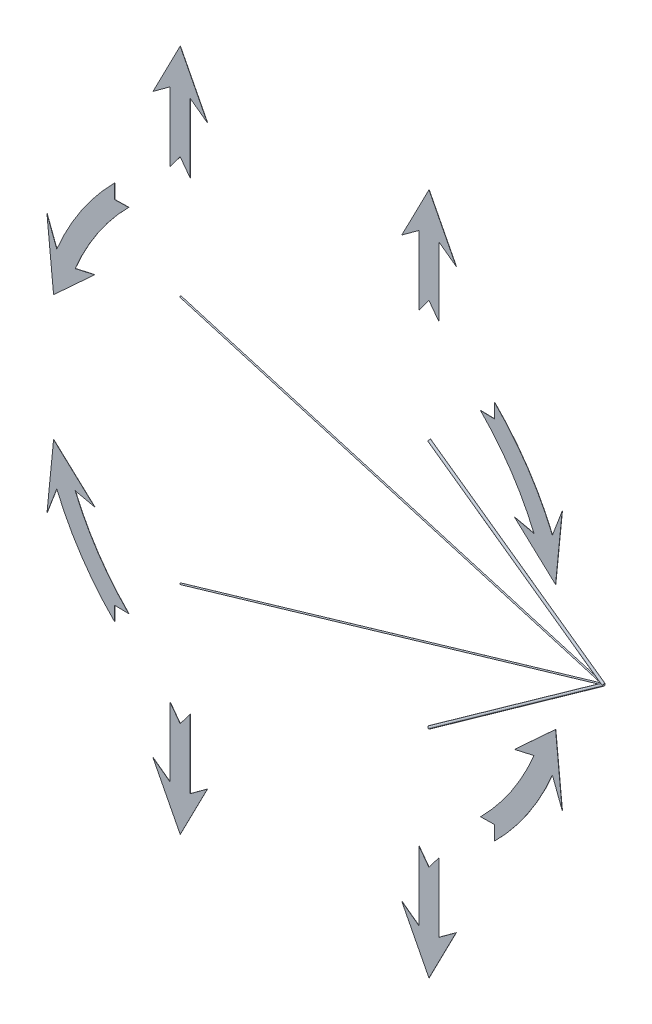
SolidWorks part; units mm, degrees
ref_plane "前视基准面" through (0, 0, 0) normal (0, 0, 1) x (1, 0, 0)
ref_plane "上视基准面" through (0, 0, 0) normal (0, 1, 0) x (1, 0, 0)
ref_plane "右视基准面" through (0, 0, 0) normal (1, 0, 0) x (0, 0, -1)
other "Configuration Table"
sketch "草图1" plane through (0, 0, 0) normal (0, 0, 1) x (1, 0, 0)
  line L0 (-76.3675, 76.3675) -> (-76.3675, 70.5975)
  line L1 (-76.3675, 70.5975) -> (-70.7107, 70.7107)
  line L2 (-76.3675, 76.3675) -> (-70.7107, 70.7107) construction
  line L3 (-70.7107, 70.7107) -> (0, 0) construction
  line L4 (0, 0) -> (0, 132.6052) construction
  line L10 (-103.5474, 52.0814) -> (-99.6085, 41.7391)
  line L11 (-103.5474, 52.0814) -> (-100.8939, 25.2272)
  line L12 (-100.8939, 25.2272) -> (-84.3936, 40.4158)
  line L13 (-84.3936, 40.4158) -> (-92.2271, 38.6543)
  circle A0 centre (0, 0) radius 100
  circle A1 centre (0, 0) radius 108
  circle A2 centre (0, 0) radius 104 construction
  dimension "D1" = 200
  dimension "D2" = 8
  dimension "D3" = 4
  dimension "D4" = 45
extrude "凸台-拉伸1" add sketch "草图1" along normal blind 0.1 contours L0 A1 L11 L12 A0 L1 | A1 L10 L11 | L13 A0 L12
sketch "草图2" plane through (0, 0, 0) normal (0, 0, 1) x (1, 0, 0)
  line L0 (50, 50) -> (38.9819, 34.5532) construction
  line L1 (50, -50) -> (-50, -50) construction
  line L2 (50, -50) -> (50, 50) construction
  line L3 (50, 50) -> (-50, 50) construction
  line L4 (-50, -50) -> (-50, 50) construction
  line L5 (50, -50) -> (-50, 50) construction
  line L6 (50, 50) -> (-50, -50) construction
  line L7 (50, 50) -> (61.0181, 65.4468) construction
  line L8 (50, 50) -> (120.0974, 0) construction
  line L9 (120.0974, 0) -> (0, 0) construction
  line L10 (0, 0) -> (0, 62.8441) construction
  line L11 (-50, 50) -> (120.0974, 0)
  point P0 (0, 0)
  dimension "D1" = 100
  dimension "D2" = 35.5
sweep "扫描1" add path "草图2" circular profile diameter 0.5 parameters "D3"=0.5
sketch "草图10" plane through (0, 0, 0) normal (0, 0, 1) x (1, 0, 0)
  line L0 (50, 50) -> (120.0974, 0) construction
  line L1 (50, 50) -> (120.0974, 0)
sweep "扫描3" add path "草图10" circular profile diameter 1 parameters "D3"=1
mirror "镜向3" about plane through (0, 0, 0) normal (0, 1, 0) of bodies 106 112
mirror "镜向4" about plane through (0, 0, 0) normal (1, 0, 0) of bodies 106 113
sketch "草图27" plane through (0, 0, 0) normal (0, 0, 1) x (1, 0, 0)
  line L0 (-50, 50) -> (-50, 137.1984) construction
  line L1 (-50, 137.1984) -> (-60.9263, 115.9808)
  line L2 (-60.9263, 115.9808) -> (-54, 121.0471)
  line L3 (-54, 121.0471) -> (-54, 93.3139)
  line L4 (-54, 93.3139) -> (-50, 98.688)
  line L5 (-46, 93.3139) -> (-50, 98.688)
  line L6 (-46, 121.0471) -> (-46, 93.3139)
  line L7 (-39.0737, 115.9808) -> (-46, 121.0471)
  line L8 (-50, 137.1984) -> (-39.0737, 115.9808)
  line L9 (-28.899, 0) -> (0, 0) construction
  line L10 (0, 0) -> (0, 75.806) construction
  line L11 (50, 137.1984) -> (39.0737, 115.9808)
  line L12 (39.0737, 115.9808) -> (46, 121.0471)
  line L13 (46, 121.0471) -> (46, 93.3139)
  line L14 (46, 93.3139) -> (50, 98.688)
  line L15 (54, 93.3139) -> (50, 98.688)
  line L16 (54, 121.0471) -> (54, 93.3139)
  line L17 (60.9263, 115.9808) -> (54, 121.0471)
  line L18 (50, 137.1984) -> (60.9263, 115.9808)
  line L19 (50, -137.1984) -> (60.9263, -115.9808)
  line L20 (60.9263, -115.9808) -> (54, -121.0471)
  line L21 (54, -121.0471) -> (54, -93.3139)
  line L22 (54, -93.3139) -> (50, -98.688)
  line L23 (46, -93.3139) -> (50, -98.688)
  line L24 (46, -121.0471) -> (46, -93.3139)
  line L25 (39.0737, -115.9808) -> (46, -121.0471)
  line L26 (50, -137.1984) -> (39.0737, -115.9808)
  line L27 (-50, -137.1984) -> (-39.0737, -115.9808)
  line L28 (-39.0737, -115.9808) -> (-46, -121.0471)
  line L29 (-46, -121.0471) -> (-46, -93.3139)
  line L30 (-46, -93.3139) -> (-50, -98.688)
  line L31 (-54, -93.3139) -> (-50, -98.688)
  line L32 (-54, -121.0471) -> (-54, -93.3139)
  line L33 (-60.9263, -115.9808) -> (-54, -121.0471)
  line L34 (-50, -137.1984) -> (-60.9263, -115.9808)
  point P38 (-54, 89.0639)
  point P39 (-50, 94.4238)
  point P40 (-50, 98.1024)
  point P41 (0, 0)
  point P42 (-46, 93.3139)
  dimension "D1" = 8
extrude "凸台-拉伸2" add sketch "草图27" along normal blind 0.1 separate body
